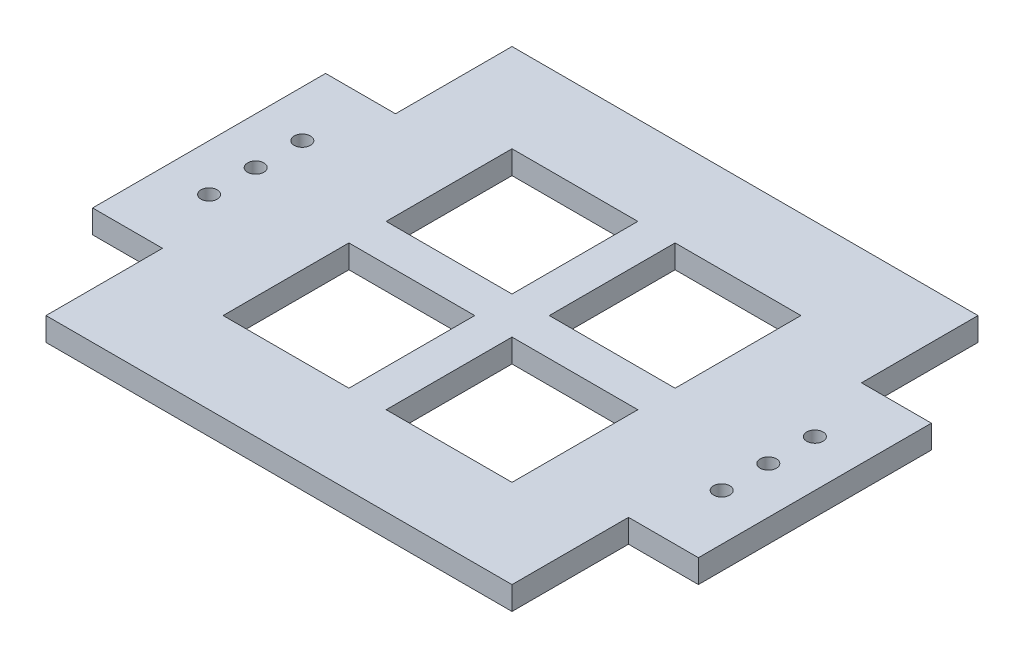
SolidWorks part; units mm, degrees
ref_plane "Front Plane" through (0, 0, 0) normal (0, 0, 1) x (1, 0, 0)
ref_plane "Top Plane" through (0, 0, 0) normal (0, 1, 0) x (1, 0, 0)
ref_plane "Right Plane" through (0, 0, 0) normal (1, 0, 0) x (0, 0, -1)
sketch "Sketch1" plane through (0, 0, 0) normal (0, 1, 0) x (1, 0, 0)
  line L1 (0, 0) -> (200, 0)
  line L2 (0, 0) -> (0, 100)
  line L3 (0, 100) -> (200, 100)
  line L4 (200, 0) -> (200, 100)
  dimension "D1" = 200
  dimension "D2" = 100
extrude "Boss-Extrude1" add sketch "Sketch1" along normal blind 5
sketch "Sketch2" plane through (0, 5, 0) normal (0, 1, 0) x (1, 0, 0)
  line L0 (200, 50) -> (158.6738, 50)
  line L1 (200, 100) -> (0, 100) construction
  line L2 (0, 0) -> (200, 0) construction
  line L4 (100, 0) -> (100, 100)
  line L5 (200, 0) -> (200, 100) construction
  circle A4 centre (170, 60) radius 1.75
  circle A5 centre (170, 40) radius 1.75
  circle A6 centre (30, 40) radius 1.75
  circle A7 centre (30, 60) radius 1.75
  circle A8 centre (155, 40) radius 1.75
  circle A9 centre (155, 60) radius 1.75
  circle A10 centre (45, 60) radius 1.75
  circle A11 centre (45, 40) radius 1.75
  dimension "D1" = 20
  dimension "D3" = 3.5
  dimension "D4" = 3.5
  dimension "D2" = 10
  dimension "D5" = 15
  dimension "D6" = 3.5
extrude "Cut-Extrude1" cut sketch "Sketch2" against normal through all contours A6 | A5 | A4 | A8 | A9 | A10
sketch "Sketch3" plane through (0, 5, 0) normal (0, 1, 0) x (1, 0, 0)
  line L0 (0, 0) -> (200, 0) construction
  line L1 (65, 0) -> (135, 0)
  line L3 (65, 10) -> (135, 10)
  line L4 (135, 0) -> (135, 10)
  line L5 (0, 50) -> (200, 50)
  line L6 (0, 100) -> (0, 0) construction
  line L7 (200, 0) -> (200, 100) construction
  line L8 (65, 90) -> (135, 90)
  line L10 (65, 100) -> (135, 100)
  line L12 (200, 100) -> (0, 100) construction
  line L13 (135, 0) -> (145, 0)
  line L14 (135, 0) -> (135, 90)
  line L15 (135, 100) -> (145, 100)
  line L16 (145, 0) -> (145, 100)
  line L17 (100, 100) -> (100, 0)
  line L18 (65, 100) -> (55, 100)
  line L19 (55, 0) -> (55, 100)
  line L20 (65, 0) -> (55, 0)
  line L21 (65, 90) -> (65, 10)
  point P12 (135, 5)
  line M13 (0, 0) -> (200, 0)
  line M15 (200, 100) -> (0, 100)
  dimension "D1" = 10
  dimension "D2" = 65
  dimension "D4" = 10
extrude "Boss-Extrude2" [suppressed] add sketch "Sketch3" along normal blind 10 contours L21 L8 L17 L10 L19 L5 M15 | L21 L5 L19 L17 L3 M13 | L3 L17 L1 L4 | L16 L5 L14 L4 M13 | L17 L8 L14 L5 L16 M15
sketch "Sketch4" plane through (0, 5, 0) normal (0, 1, 0) x (1, 0, 0)
  line L0 (200, 0) -> (200, 100) construction
  line L1 (0, 100) -> (0, 0) construction
  circle A0 centre (155, 50) radius 1.75
  circle A1 centre (45, 50) radius 1.75
  dimension "D1" = 3.5
  dimension "D2" = 45
  dimension "D3" = 3.5
  dimension "D4" = 45
extrude "Cut-Extrude2" cut sketch "Sketch4" against normal through all
sketch "Sketch5" plane through (0, 5, 0) normal (0, 1, 0) x (1, 0, 0)
  line L0 (0, 100) -> (0, 0) construction
  line L1 (5, 65) -> (15, 65)
  line L2 (5, 65) -> (5, 35)
  line L3 (5, 35) -> (15, 35)
  line L4 (15, 65) -> (15, 35)
  line L5 (0, 0) -> (200, 0) construction
  line L6 (200, 100) -> (0, 100) construction
  line L7 (100, 100) -> (100, 0)
  line L8 (195, 35) -> (185, 35)
  line L9 (185, 65) -> (185, 35)
  line L10 (195, 65) -> (185, 65)
  line L11 (195, 65) -> (195, 35)
  dimension "D1" = 5
  dimension "D2" = 35
  dimension "D3" = 35
  dimension "D4" = 10
extrude "Cut-Extrude3" [suppressed] cut sketch "Sketch5" against normal through all contours L4 L1 L2 L3 | L11 L10 L9 L8
sketch "Sketch6" plane through (0, 5, 0) normal (0, 1, 0) x (1, 0, 0)
  line L0 (0, 0) -> (200, 0) construction
  line L1 (65, 85) -> (135, 85)
  line L2 (65, 85) -> (65, 15)
  line L3 (65, 15) -> (135, 15)
  line L4 (135, 85) -> (135, 15)
  line L5 (200, 100) -> (0, 100) construction
  line L6 (200, 50) -> (0, 50)
  line L7 (200, 100) -> (150, 100)
  line L8 (200, 100) -> (200, 75)
  line L9 (200, 75) -> (150, 75)
  line L10 (150, 100) -> (150, 75)
  line L13 (100, 0) -> (100, 100)
  line L14 (200, 0) -> (200, 100) construction
  line L15 (0, 100) -> (0, 0) construction
  line L16 (200, 25) -> (150, 25)
  line L17 (150, 0) -> (150, 25)
  line L18 (200, 0) -> (150, 0)
  line L19 (200, 0) -> (200, 25)
  line L20 (0, 0) -> (0, 25)
  line L21 (0, 0) -> (50, 0)
  line L22 (50, 0) -> (50, 25)
  line L23 (0, 25) -> (50, 25)
  line L24 (0, 75) -> (50, 75)
  line L25 (50, 100) -> (50, 75)
  line L26 (0, 100) -> (50, 100)
  line L27 (0, 100) -> (0, 75)
  line L28 (131, 54) -> (104, 54)
  line L29 (131, 19) -> (104, 19)
  line L30 (131, 19) -> (131, 46)
  line L31 (131, 46) -> (104, 46)
  line L32 (104, 19) -> (104, 46)
  line L33 (104, 81) -> (104, 54)
  line L34 (131, 81) -> (104, 81)
  line L35 (131, 81) -> (131, 54)
  line L36 (69, 46) -> (96, 46)
  line L37 (96, 19) -> (96, 46)
  line L38 (69, 19) -> (96, 19)
  line L39 (69, 19) -> (69, 46)
  line L40 (69, 81) -> (69, 54)
  line L41 (69, 81) -> (96, 81)
  line L42 (96, 81) -> (96, 54)
  line L43 (69, 54) -> (96, 54)
  circle A0 centre (45, 50) radius 1.75 construction
  circle A1 centre (155, 50) radius 1.75 construction
  line M24 (0, 100) -> (0, 0)
  line M25 (0, 0) -> (200, 0)
  line M26 (200, 0) -> (200, 100)
  line M27 (200, 100) -> (0, 100)
  dimension "D2" = 20
  dimension "D1" = 20
  dimension "D3" = 15
  dimension "D4" = 15
  dimension "D5" = 25
  dimension "D6" = 50
  dimension "D7" = 4
  dimension "D8" = 4
  dimension "D9" = 4
  dimension "D10" = 4
extrude "Cut-Extrude4" cut sketch "Sketch6" against normal through all contours L23 L22 M24 M25 | L25 L24 M27 M24 | L40 L43 L42 L41 | L35 L34 L33 L28 | L39 L38 L37 L36 | L32 L29 L30 L31 | L10 L9 M27 M26 | L17 L16 M25 M26
sketch "Sketch7" plane through (0, 5, 0) normal (0, 1, 0) x (1, 0, 0)
  line L0 (200, 25) -> (150, 25) construction
  line L1 (165, 25) -> (200, 25)
  line L2 (165, 25) -> (165, 75)
  line L3 (165, 75) -> (200, 75)
  line L4 (200, 25) -> (200, 75)
  line L5 (100, 100) -> (100, 0)
  line L6 (150, 100) -> (50, 100) construction
  line L7 (50, 0) -> (150, 0) construction
  line L8 (35, 75) -> (0, 75)
  line L9 (0, 25) -> (0, 75)
  line L10 (35, 25) -> (0, 25)
  line L11 (35, 25) -> (35, 75)
  circle M15 centre (170, 60) radius 1.75
  circle M16 centre (30, 40) radius 1.75
  circle M17 centre (170, 40) radius 1.75
  circle M19 centre (30, 60) radius 1.75
  line M24 (50, 75) -> (0, 75)
  line M25 (0, 75) -> (0, 25)
  line M26 (0, 25) -> (50, 25)
  line M30 (150, 25) -> (200, 25)
  line M31 (200, 25) -> (200, 75)
  line M32 (200, 75) -> (150, 75)
  dimension "D1" = 65
extrude "Cut-Extrude5" cut sketch "Sketch7" against normal through all contours L2 M30 M31 M32 M17 M15 | L11 M26 M24 M25 M16 M19
